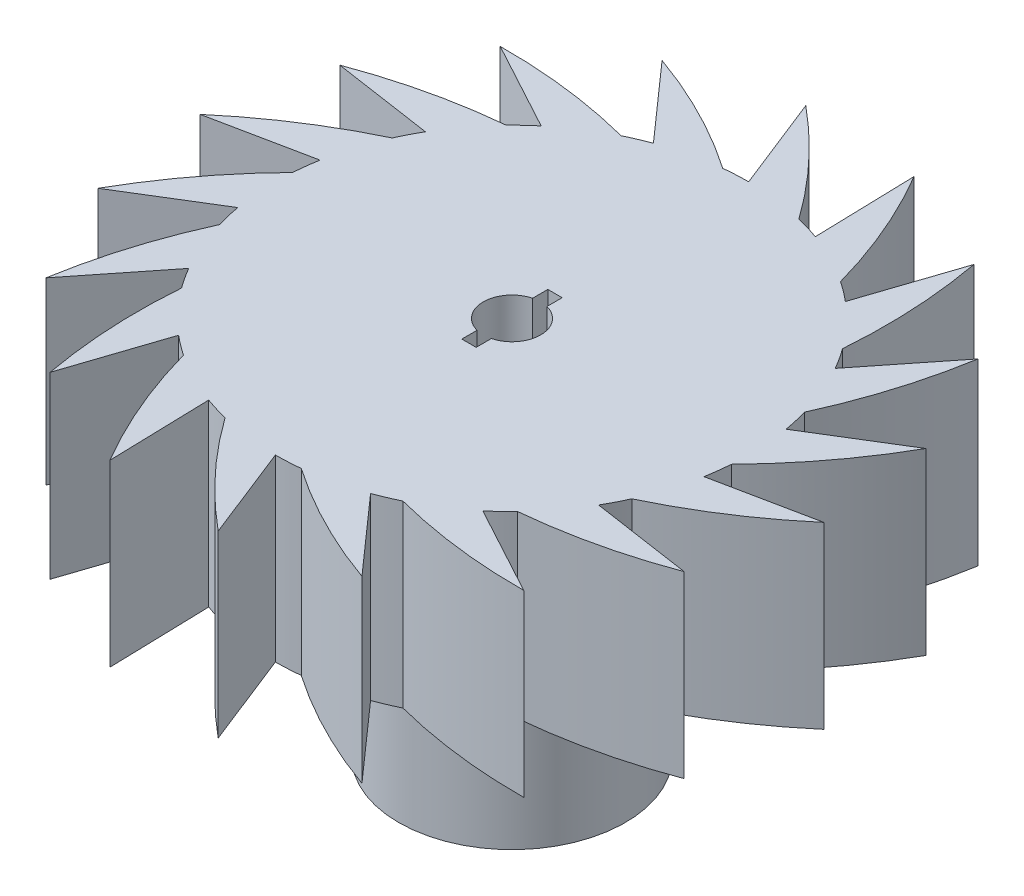
SolidWorks part; units mm, degrees
ref_plane "Front Plane" through (0, 0, 0) normal (0, 0, 1) x (1, 0, 0)
ref_plane "Top Plane" through (0, 0, 0) normal (0, 1, 0) x (1, 0, 0)
ref_plane "Right Plane" through (0, 0, 0) normal (1, 0, 0) x (0, 0, -1)
sketch "Sketch1" plane through (0, 0, 0) normal (0, 1, 0) x (1, 0, 0)
  circle A0 centre (0, 0) radius 15
ref_plane "Plane1" through (0, 0, 0) normal (0, 1, 0) x (1, 0, 0)
sketch "Sketch2" plane through (0, 0, 0) normal (0, 1, 0) x (1, 0, 0)
  circle A0 centre (0, 0) radius 3.95
extrude "Boss-Extrude1" add sketch "Sketch2" along normal blind 13.25
sketch "Sketch3" plane through (0, 13.25, 0) normal (0, 1, 0) x (1, 0, 0)
  circle A0 centre (0, 0) radius 8.25
extrude "Boss-Extrude2" add sketch "Sketch3" against normal blind 6.25
ref_plane "Plane2" through (0, 7, 0) normal (0, 1, 0) x (1, 0, 0)
sketch "Sketch4" plane through (0, 7, 0) normal (0, 1, 0) x (1, 0, 0)
  line L0 (0, 0) -> (0, 15) construction
  line L1 (0, 0) -> (15, 0) construction
  line L2 (0, 8.25) -> (-1.3015, 11.5451)
  line L3 (2, 8.0039) -> (0, 8.25)
  line L6 (2.8217, 7.7525) -> (2.7257, 11.294)
  line L7 (4.6169, 6.8372) -> (2.8217, 7.7525)
  line L10 (0, 0) -> (5.1303, 14.0954) construction
  line L11 (0, 0) -> (14.0954, -5.1303) construction
  line L14 (0, 0) -> (15, 0) construction
  line L15 (0, 0) -> (14.0954, -5.1303) construction
  line L18 (0, 0) -> (5.1303, 14.0954) construction
  line L19 (5.303, 6.3199) -> (6.4241, 9.6806)
  line L22 (6.6769, 4.8458) -> (5.303, 6.3199)
  line L23 (0, 0) -> (9.6418, 11.4907) construction
  line L26 (0, 0) -> (11.4907, -9.6418) construction
  line L27 (0, 0) -> (11.4907, -9.6418) construction
  line L30 (0, 0) -> (9.6418, 11.4907) construction
  line L31 (7.1447, 4.125) -> (9.3477, 6.8997)
  line L34 (7.9316, 2.2699) -> (7.1447, 4.125)
  line L35 (0, 0) -> (12.9904, 7.5) construction
  line L38 (0, 0) -> (7.5, -12.9904) construction
  line L39 (0, 0) -> (0, 15) construction
  line L42 (0, 0) -> (7.5, -12.9904) construction
  line L43 (0, 0) -> (12.9904, 7.5) construction
  line L46 (8.1247, 1.4326) -> (11.1437, 3.2865)
  line L47 (8.2296, -0.5798) -> (8.1247, 1.4326)
  line L48 (4.125, 7.1447) -> (4.6455, 10.6491) [skipped]
  line L49 (5.734, 5.9316) -> (4.125, 7.1447) [skipped]
  line L50 (0, 0) -> (12.9904, 7.5) construction
  line L51 (7.1447, 4.125) -> (9.3477, 6.8997) [skipped]
  line L52 (7.9316, 2.2699) -> (7.1447, 4.125) [skipped]
  line L53 (8.25, 0) -> (11.5451, 1.3015) [skipped]
  line L54 (8.0039, -2) -> (8.25, 0) [skipped]
  line L55 (7.1447, -4.125) -> (10.6491, -4.6455) [skipped]
  line L56 (5.9316, -5.734) -> (7.1447, -4.125) [skipped]
  line L57 (4.125, -7.1447) -> (6.8997, -9.3477) [skipped]
  line L58 (2.2699, -7.9316) -> (4.125, -7.1447) [skipped]
  line L59 (0, -8.25) -> (1.3015, -11.5451) [skipped]
  line L60 (-2, -8.0039) -> (0, -8.25) [skipped]
  line L61 (-4.125, -7.1447) -> (-4.6455, -10.6491) [skipped]
  line L62 (-5.734, -5.9316) -> (-4.125, -7.1447) [skipped]
  line L63 (-7.1447, -4.125) -> (-9.3477, -6.8997) [skipped]
  line L64 (-7.9316, -2.2699) -> (-7.1447, -4.125) [skipped]
  line L65 (-8.25, 0) -> (-11.5451, -1.3015) [skipped]
  line L66 (-8.0039, 2) -> (-8.25, 0) [skipped]
  line L67 (-7.1447, 4.125) -> (-10.6491, 4.6455) [skipped]
  line L68 (-5.9316, 5.734) -> (-7.1447, 4.125) [skipped]
  line L69 (-4.125, 7.1447) -> (-6.8997, 9.3477) [skipped]
  line L70 (-2.2699, 7.9316) -> (-4.125, 7.1447) [skipped]
  line L71 (0, 0) -> (7.5, 12.9904) construction
  line L72 (0, 0) -> (12.9904, 7.5) construction
  line L73 (0, 0) -> (7.5, 12.9904) construction
  line L74 (0, 0) -> (-7.5, 12.9904) construction
  line L75 (0, 0) -> (-12.9904, 7.5) construction
  line L76 (0, 0) -> (-15, 0) construction
  line L77 (0, 0) -> (-12.9904, 7.5) construction
  line L78 (0, 0) -> (-7.5, 12.9904) construction
  line L79 (0, 0) -> (-15, 0) construction
  line L80 (0, 0) -> (-12.9904, -7.5) construction
  line L81 (0, 0) -> (-7.5, -12.9904) construction
  line L82 (0, 0) -> (-12.9904, -7.5) construction
  line L83 (0, 0) -> (-7.5, -12.9904) construction
  line L84 (0, 0) -> (0, -15) construction
  line L85 (0, 0) -> (7.5, -12.9904) construction
  line L86 (0, 0) -> (0, -15) construction
  line L87 (0, 0) -> (7.5, -12.9904) construction
  line L88 (0, 0) -> (12.9904, -7.5) construction
  line L89 (0, 0) -> (12.9904, -7.5) construction
  line L90 (0, 0) -> (14.7721, 2.6047) construction
  line L91 (0, 0) -> (2.6047, -14.7721) construction
  line L92 (0, 0) -> (2.6047, -14.7721) construction
  line L93 (0, 0) -> (14.7721, 2.6047) construction
  line L94 (8.1247, -1.4326) -> (11.5957, -0.7231)
  line L95 (7.535, -3.3595) -> (8.1247, -1.4326)
  line L96 (0, 0) -> (14.7721, -2.6047) construction
  line L97 (0, 0) -> (-2.6047, -14.7721) construction
  line L98 (0, 0) -> (-2.6047, -14.7721) construction
  line L99 (0, 0) -> (14.7721, -2.6047) construction
  line L100 (7.1447, -4.125) -> (10.6491, -4.6455)
  line L101 (5.9316, -5.734) -> (7.1447, -4.125)
  line L102 (0, 0) -> (12.9904, -7.5) construction
  line L103 (0, 0) -> (-7.5, -12.9904) construction
  line L104 (0, 0) -> (-7.5, -12.9904) construction
  line L105 (0, 0) -> (12.9904, -7.5) construction
  line L106 (5.303, -6.3199) -> (8.418, -8.0075)
  line L107 (3.6127, -7.4169) -> (5.303, -6.3199)
  line L108 (0, 0) -> (9.6418, -11.4907) construction
  line L109 (0, 0) -> (-11.4907, -9.6418) construction
  line L110 (0, 0) -> (-11.4907, -9.6418) construction
  line L111 (0, 0) -> (9.6418, -11.4907) construction
  line L112 (2.8217, -7.7525) -> (5.1716, -10.4038)
  line L113 (0.8581, -8.2053) -> (2.8217, -7.7525)
  line L114 (0, 0) -> (5.1303, -14.0954) construction
  line L115 (0, 0) -> (-14.0954, -5.1303) construction
  line L116 (0, 0) -> (-14.0954, -5.1303) construction
  line L117 (0, 0) -> (5.1303, -14.0954) construction
  line L118 (0, -8.25) -> (1.3015, -11.5451)
  line L119 (-2, -8.0039) -> (0, -8.25)
  line L120 (0, 0) -> (0, -15) construction
  line L121 (0, 0) -> (-15, 0) construction
  line L122 (0, 0) -> (-15, 0) construction
  line L123 (0, 0) -> (0, -15) construction
  line L124 (-2.8217, -7.7525) -> (-2.7257, -11.294)
  line L125 (-4.6169, -6.8372) -> (-2.8217, -7.7525)
  line L126 (0, 0) -> (-5.1303, -14.0954) construction
  line L127 (0, 0) -> (-14.0954, 5.1303) construction
  line L128 (0, 0) -> (-14.0954, 5.1303) construction
  line L129 (0, 0) -> (-5.1303, -14.0954) construction
  line L130 (-5.303, -6.3199) -> (-6.4241, -9.6806)
  line L131 (-6.6769, -4.8458) -> (-5.303, -6.3199)
  line L132 (0, 0) -> (-9.6418, -11.4907) construction
  line L133 (0, 0) -> (-11.4907, 9.6418) construction
  line L134 (0, 0) -> (-11.4907, 9.6418) construction
  line L135 (0, 0) -> (-9.6418, -11.4907) construction
  line L136 (-7.1447, -4.125) -> (-9.3477, -6.8997)
  line L137 (-7.9316, -2.2699) -> (-7.1447, -4.125)
  line L138 (0, 0) -> (-12.9904, -7.5) construction
  line L139 (0, 0) -> (-7.5, 12.9904) construction
  line L140 (0, 0) -> (-7.5, 12.9904) construction
  line L141 (0, 0) -> (-12.9904, -7.5) construction
  line L142 (-8.1247, -1.4326) -> (-11.1437, -3.2865)
  line L143 (-8.2296, 0.5798) -> (-8.1247, -1.4326)
  line L144 (0, 0) -> (-14.7721, -2.6047) construction
  line L145 (0, 0) -> (-2.6047, 14.7721) construction
  line L146 (0, 0) -> (-2.6047, 14.7721) construction
  line L147 (0, 0) -> (-14.7721, -2.6047) construction
  line L148 (-8.1247, 1.4326) -> (-11.5957, 0.7231)
  line L149 (-7.535, 3.3595) -> (-8.1247, 1.4326)
  line L150 (0, 0) -> (-14.7721, 2.6047) construction
  line L151 (0, 0) -> (2.6047, 14.7721) construction
  line L152 (0, 0) -> (2.6047, 14.7721) construction
  line L153 (0, 0) -> (-14.7721, 2.6047) construction
  line L154 (-7.1447, 4.125) -> (-10.6491, 4.6455)
  line L155 (-5.9316, 5.734) -> (-7.1447, 4.125)
  line L156 (0, 0) -> (-12.9904, 7.5) construction
  line L157 (0, 0) -> (7.5, 12.9904) construction
  line L158 (0, 0) -> (7.5, 12.9904) construction
  line L159 (0, 0) -> (-12.9904, 7.5) construction
  line L160 (-5.303, 6.3199) -> (-8.418, 8.0075)
  line L161 (-3.6127, 7.4169) -> (-5.303, 6.3199)
  line L162 (0, 0) -> (-9.6418, 11.4907) construction
  line L163 (0, 0) -> (11.4907, 9.6418) construction
  line L164 (0, 0) -> (11.4907, 9.6418) construction
  line L165 (0, 0) -> (-9.6418, 11.4907) construction
  line L166 (-2.8217, 7.7525) -> (-5.1716, 10.4038)
  line L167 (-0.8581, 8.2053) -> (-2.8217, 7.7525)
  line L168 (0, 0) -> (-5.1303, 14.0954) construction
  line L169 (0, 0) -> (14.0954, 5.1303) construction
  line L170 (0, 0) -> (14.0954, 5.1303) construction
  line L171 (0, 0) -> (-5.1303, 14.0954) construction
  circle A0 centre (0, 0) radius 15 construction
  circle A1 centre (0, 0) radius 8.25 construction
  arc A2 (-1.3015, 11.5451) -> (2, 8.0039) centre (-13.0603, -2.727) cw
  arc A14 (4.6455, 10.6491) -> (5.734, 5.9316) centre (-12.674, 4.1685) cw [skipped]
  arc A15 (9.3477, 6.8997) -> (7.9316, 2.2699) centre (-8.8918, 9.947) cw [skipped]
  arc A16 (11.5451, 1.3015) -> (8.0039, -2) centre (-2.727, 13.0603) cw [skipped]
  arc A17 (10.6491, -4.6455) -> (5.9316, -5.734) centre (4.1685, 12.674) cw [skipped]
  arc A18 (6.8997, -9.3477) -> (2.2699, -7.9316) centre (9.947, 8.8918) cw [skipped]
  arc A19 (1.3015, -11.5451) -> (-2, -8.0039) centre (13.0603, 2.727) cw [skipped]
  arc A20 (-4.6455, -10.6491) -> (-5.734, -5.9316) centre (12.674, -4.1685) cw [skipped]
  arc A21 (-9.3477, -6.8997) -> (-7.9316, -2.2699) centre (8.8918, -9.947) cw [skipped]
  arc A22 (-11.5451, -1.3015) -> (-8.0039, 2) centre (2.727, -13.0603) cw [skipped]
  arc A23 (-10.6491, 4.6455) -> (-5.9316, 5.734) centre (-4.1685, -12.674) cw [skipped]
  arc A24 (-6.8997, 9.3477) -> (-2.2699, 7.9316) centre (-9.947, -8.8918) cw [skipped]
  arc A25 (2.7257, 11.294) -> (4.6169, 6.8372) centre (-13.2053, 1.9043) cw
  arc A26 (6.4241, 9.6806) -> (6.6769, 4.8458) centre (-11.7577, 6.3059) cw
  arc A27 (9.3477, 6.8997) -> (7.9316, 2.2699) centre (-8.8918, 9.947) cw
  arc A28 (11.1437, 3.2865) -> (8.2296, -0.5798) centre (-4.9535, 12.3883) cw
  arc A29 (11.5957, -0.7231) -> (7.535, -3.3595) centre (-0.4177, 13.3354) cw
  arc A30 (10.6491, -4.6455) -> (5.9316, -5.734) centre (4.1685, 12.674) cw
  arc A31 (8.418, -8.0075) -> (3.6127, -7.4169) centre (8.2518, 10.484) cw
  arc A32 (5.1716, -10.4038) -> (0.8581, -8.2053) centre (11.3399, 7.0295) cw
  arc A33 (1.3015, -11.5451) -> (-2, -8.0039) centre (13.0603, 2.727) cw
  arc A34 (-2.7257, -11.294) -> (-4.6169, -6.8372) centre (13.2053, -1.9043) cw
  arc A35 (-6.4241, -9.6806) -> (-6.6769, -4.8458) centre (11.7577, -6.3059) cw
  arc A36 (-9.3477, -6.8997) -> (-7.9316, -2.2699) centre (8.8918, -9.947) cw
  arc A37 (-11.1437, -3.2865) -> (-8.2296, 0.5798) centre (4.9535, -12.3883) cw
  arc A38 (-11.5957, 0.7231) -> (-7.535, 3.3595) centre (0.4177, -13.3354) cw
  arc A39 (-10.6491, 4.6455) -> (-5.9316, 5.734) centre (-4.1685, -12.674) cw
  arc A40 (-8.418, 8.0075) -> (-3.6127, 7.4169) centre (-8.2518, -10.484) cw
  arc A41 (-5.1716, 10.4038) -> (-0.8581, 8.2053) centre (-11.3399, -7.0295) cw
  point P22 (0, 0)
  point P32 (0, 0)
  point P41 (0, 0)
  point P50 (0, 0)
  point P59 (0, 0)
  point P69 (0, 0)
  point P78 (0, 0)
  point P81 (0, 0)
  point P171 (0, 0)
  point P189 (0, 0)
  point P203 (0, 0)
  point P212 (0, 0)
  point P221 (0, 0)
  point P230 (0, 0)
  point P239 (0, 0)
  point P248 (0, 0)
  point P257 (0, 0)
  point P266 (0, 0)
  point P267 (0, 0)
  dimension "D2" = 18
  dimension "D1" = 12
sketch "Sketch5" plane through (0, 13.25, 0) normal (0, 1, 0) x (1, 0, 0)
  line L0 (0.25, -0.9682) -> (0.25, -1.5)
  line L1 (-0.25, 1.5) -> (0.25, 1.5)
  line L2 (-0.25, 1.5) -> (-0.25, 0.9682)
  line L3 (-0.25, -1.5) -> (0.25, -1.5)
  line L4 (0.25, 1.5) -> (0.25, 0.9682)
  line L9 (-0.25, -0.9682) -> (-0.25, -1.5)
  arc A1 (-0.25, 0.9682) -> (-0.25, -0.9682) centre (0, 0) ccw
  arc A2 (0.25, -0.9682) -> (0.25, 0.9682) centre (0, 0) ccw
  dimension "D1" = 0.5
  dimension "D2" = 3
extrude "Cut-Extrude1" cut sketch "Sketch5" against normal blind 4
extrude "Boss-Extrude3" add sketch "Sketch4" along normal blind 6.25
